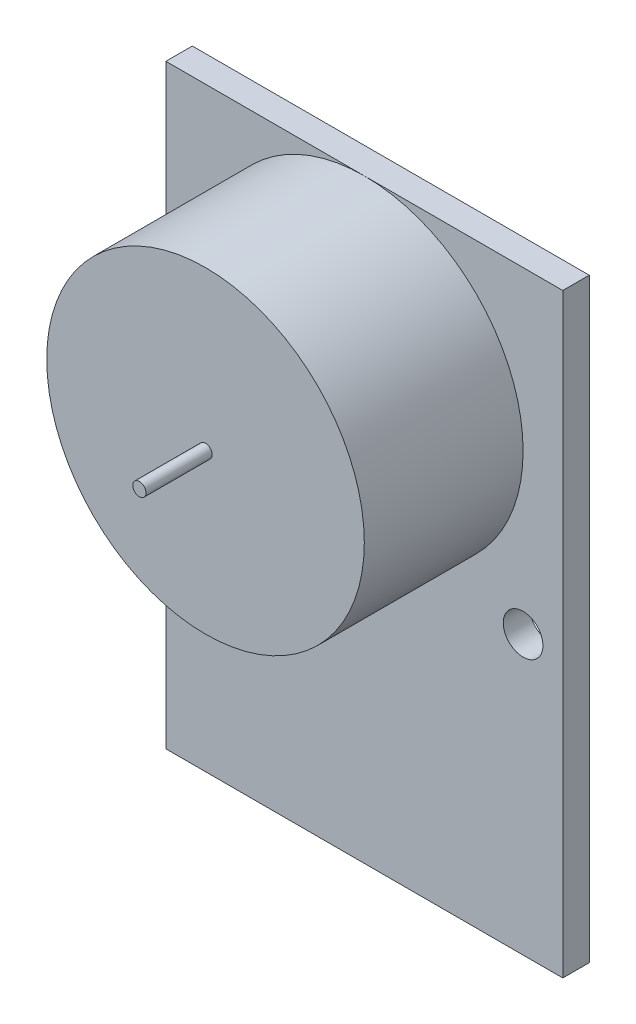
SolidWorks part; units mm, degrees
ref_plane "前视基准面" through (0, 0, 0) normal (0, 0, 1) x (1, 0, 0)
ref_plane "上视基准面" through (0, 0, 0) normal (0, 1, 0) x (1, 0, 0)
ref_plane "右视基准面" through (0, 0, 0) normal (1, 0, 0) x (0, 0, -1)
sketch "草图1" plane through (0, 0, 0) normal (0, 0, 1) x (1, 0, 0)
  line L1 (-15, -22.5) -> (15, -22.5)
  line L2 (-15, -22.5) -> (-15, 22.5)
  line L3 (-15, 22.5) -> (15, 22.5)
  line L4 (15, -22.5) -> (15, 22.5)
  line L5 (-15, -22.5) -> (15, 22.5) construction
  line L6 (-15, 22.5) -> (15, -22.5) construction
  point P0 (0, 0)
  dimension "D1" = 45
  dimension "D2" = 30
sketch "草图2" plane through (0, 0, 0) normal (0, 0, 1) x (1, 0, 0)
  line L0 (0, -1286.8981) -> (0, 63058.0065) construction
  line L1 (-15, 22.5) -> (15, 22.5) construction
  circle A0 centre (0, 10.5) radius 12
  dimension "D1" = 24
sketch "草图3" plane through (0, 0, 0) normal (0, 0, 1) x (1, 0, 0)
  line L0 (-12, -1005.6157) -> (-12, 48994.3843) construction
  line L1 (-1012, -1.5) -> (48988, -1.5) construction
  line L2 (0, -997.0293) -> (0, 49002.9707) construction
  circle A0 centre (-12, -1.5) radius 1.5
  circle A1 centre (0, 10.5) radius 12 construction
  circle A2 centre (12, -1.5) radius 1.5
  dimension "D1" = 3
extrude "凸台-拉伸1" add sketch "草图1" against normal blind 2
extrude "凸台-拉伸2" add sketch "草图2" along normal blind 12
extrude "切除-拉伸1" cut sketch "草图3" against normal up to next
ref_plane "基准面1" through (0, 0, 12) normal (0, 0, 1) x (1, 0, 0)
sketch "草图5" plane through (0, 0, 12) normal (0, 0, 1) x (1, 0, 0)
  circle A0 centre (0, 10.5) radius 12 construction
  circle A1 centre (0, 10.5) radius 0.5
  point P0 (0, 10.5)
  dimension "D1" = 1
extrude "凸台-拉伸3" add sketch "草图5" along normal blind 5
